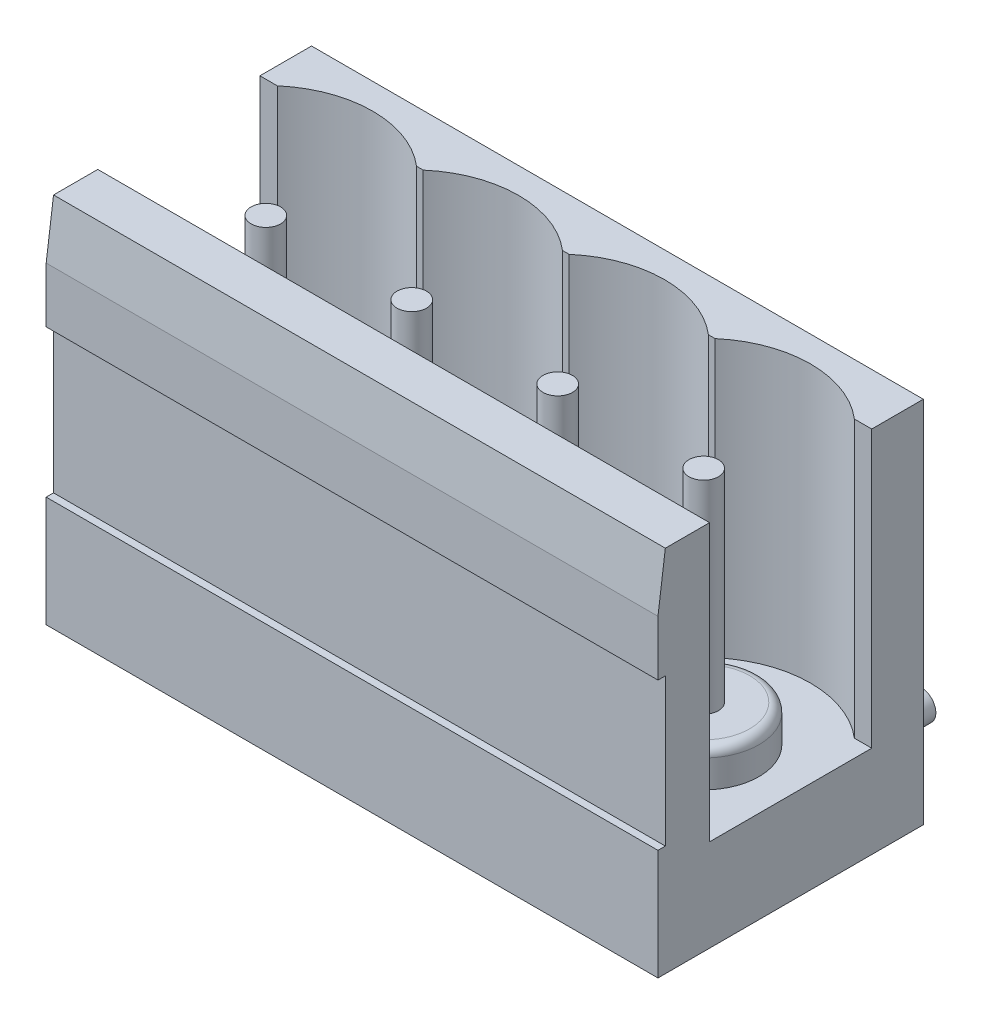
SolidWorks part; units mm, degrees
ref_plane "前视基准面" through (0, 0, 0) normal (0, 0, 1) x (1, 0, 0)
ref_plane "上视基准面" through (0, 0, 0) normal (0, 1, 0) x (1, 0, 0)
ref_plane "右视基准面" through (0, 0, 0) normal (1, 0, 0) x (0, 0, -1)
sketch "草图1" plane through (0, 0, 0) normal (0, 0, 1) x (1, 0, 0)
  line L0 (0, 0) -> (16.6, 0)
  line L1 (16.6, 0) -> (16.6, 10)
  line L2 (16.6, 10) -> (0, 10)
  line L3 (0, 10) -> (0, 0)
  dimension "D1" = 16.6
  dimension "D2" = 10
extrude "凸台-拉伸1" add sketch "草图1" along normal blind 7.2
sketch "草图2" plane through (16.6, 0, 0) normal (1, 0, 0) x (0, 0, -1)
  line L0 (-8.1771, 3) -> (-7, 3)
  line L1 (-7, 3) -> (-7, 7)
  line L2 (-7, 7) -> (-8.1771, 7)
  line L3 (-7.2, 0) -> (0, 0) construction
  line L4 (-7.2, 10) -> (0, 10) construction
  line L5 (-7.2, 0) -> (-7.2, 10) construction
  line L6 (-8.1771, 7) -> (-8.1771, 3)
  point P2 (-3.6, 0)
  dimension "D1" = 3
  dimension "D2" = 3
  dimension "D3" = 0.2
extrude "切除-拉伸1" cut sketch "草图2" against normal through all
sketch "草图3" plane through (16.6, 0, 0) normal (1, 0, 0) x (0, 0, -1)
  line L1 (-7.2, 10) -> (0, 10) construction
  line L2 (-7, 10) -> (-7.2, 8.5)
  line L3 (-7.2, 7) -> (-7.2, 10) construction
  line L4 (-7.2, 8.5) -> (-7.2, 10)
  line L5 (-7.2, 10) -> (-7, 10)
extrude "切除-拉伸2" cut sketch "草图3" against normal through all
sketch "草图6" plane through (0, 10, 0) normal (0, 1, 0) x (1, 0, 0)
  line L0 (0.3918, -1.4) -> (0, -1.4)
  line L6 (16.6, 0) -> (0, 0) construction
  line L8 (0.5, -0.8) -> (16.6, -0.8) construction
  line L9 (16.6, -7) -> (16.6, 0) construction
  line L10 (16.6, -1.4) -> (0.5, -1.4)
  line L11 (0.5, -5.8) -> (16.6, -5.8)
  line L12 (0.3918, -5.8) -> (0.5, -5.8)
  line L13 (0, -7) -> (0, 0) construction
  line L14 (0.3918, -0.8) -> (0.5, -0.8)
  line L15 (0.5, -1.4) -> (0.3918, -1.4)
  line L17 (0, -1.4) -> (-0.2811, -1.4)
  line L18 (-0.2811, -1.4) -> (-0.2811, -5.8)
  line L19 (-0.2811, -5.8) -> (0.3918, -5.8)
  line L20 (16.6, -5.8) -> (16.6, -1.4)
  line M1 (0, 0) -> (0, -7)
  line M3 (16.6, -7) -> (16.6, 0)
  dimension "D4" = 5
  dimension "D2" = 0.8
  dimension "D3" = 1.4
extrude "切除-拉伸4" cut sketch "草图6" against normal blind 7.5 contours L19 L12 L11 L10 L15 L0 M1 M3
sketch "草图12" plane through (0, 2.5, 0) normal (0, 1, 0) x (1, 0, 0)
  line L0 (16.6, -7.2) -> (16.6, 0) construction
  line L1 (16.6, -3.6) -> (0, -3.6) construction
  line L2 (0, -1.4) -> (0, -5.8) construction
  line L3 (8.3, -7) -> (8.3, 0) construction
  line L4 (0, -7) -> (16.6, -7) construction
  line L5 (16.6, 0) -> (0, 0) construction
  circle A0 centre (6.32, -3.6) radius 0.4
  circle A1 centre (2.36, -3.6) radius 0.4
  circle A2 centre (14.24, -3.6) radius 0.4
  circle A3 centre (10.28, -3.6) radius 0.4
  dimension "D1" = 0.8
  dimension "D2" = 3.96
  dimension "D3" = 2
extrude "凸台-拉伸8" add sketch "草图12" along normal blind 6.5
sketch "草图13" plane through (0, 2.5, 0) normal (0, 1, 0) x (1, 0, 0)
  circle A0 centre (14.24, -3.6) radius 1.5
  circle A1 centre (10.28, -3.6) radius 1.5
  circle A2 centre (6.32, -3.6) radius 1.5
  circle A3 centre (2.36, -3.6) radius 1.5
extrude "凸台-拉伸9" add sketch "草图13" along normal blind 1
fillet "圆角2" radius 0.25 4 edges at (2.36, 3.5, 5.1) (6.32, 3.5, 5.1) (10.28, 3.5, 5.1) (14.24, 3.5, 5.1)
sketch "草图14" plane through (0, 0, 0) normal (0, -1, 0) x (1, 0, 0)
  line L0 (0, 4.2) -> (16.6, 4.2) construction
  line L1 (0, 7.2) -> (0, 0) construction
  line L2 (16.6, 7.2) -> (16.6, 0) construction
  line L3 (0, 7.2) -> (16.6, 7.2) construction
  line L4 (8.3, 7.2) -> (8.3, 0) construction
  line L5 (0, 0) -> (16.6, 0) construction
  line L6 (10.28, 4.9755) -> (10.28, 2.6203) construction
  line L7 (9.78, 4.2) -> (9.78, 0)
  line L8 (10.78, 4.2) -> (10.78, 0)
  line L9 (9.78, 4.2) -> (10.78, 4.2)
  line L10 (9.78, 0) -> (10.78, 0)
  line L11 (10.78, 0) -> (10.788, 0.0286)
  line L12 (13.74, 4.2) -> (13.74, 0)
  line L13 (14.74, 4.2) -> (14.74, 0)
  line L14 (13.74, 4.2) -> (14.74, 4.2)
  line L15 (13.74, 0) -> (14.74, 0)
  line L16 (2.86, 0) -> (1.86, 0)
  line L17 (2.86, 4.2) -> (1.86, 4.2)
  line L18 (1.86, 4.2) -> (1.86, 0)
  line L19 (2.86, 4.2) -> (2.86, 0)
  line L20 (6.82, 0) -> (5.82, 0)
  line L21 (6.82, 4.2) -> (5.82, 4.2)
  line L22 (5.82, 4.2) -> (5.82, 0)
  line L23 (6.82, 4.2) -> (6.82, 0)
  line M1 (0, 0) -> (16.6, 0)
  dimension "D1" = 3
  dimension "D2" = 1.98
  dimension "D3" = 1
  dimension "D4" = 2
extrude "切除-拉伸7" cut sketch "草图14" against normal blind 1 contours L19 L17 L18 M1 | L23 L21 L22 M1 | L9 L7 L8 M1 | L14 L12 L13 M1
sketch "草图15" plane through (0, 0, 4.2) normal (0, 0, -1) x (-1, 0, 0)
  line L0 (-2.86, 0) -> (-1.86, 1) construction
  line L1 (-1.86, 0) -> (-2.86, 1) construction
  circle A0 centre (-2.36, 0.5) radius 0.4
  circle A1 centre (-6.32, 0.5) radius 0.4
  circle A2 centre (-10.28, 0.5) radius 0.4
  circle A3 centre (-14.24, 0.5) radius 0.4
extrude "凸台-拉伸10" add sketch "草图15" along normal blind 6.5
sketch "草图16" plane through (0, 10, 0) normal (0, 1, 0) x (1, 0, 0)
  line L0 (16.6, -0.7) -> (0, -0.7) construction
  line L1 (16.6, -1.4) -> (16.6, 0) construction
  line L2 (0, -1.4) -> (0, 0) construction
  line L3 (0.4706, -1.4) -> (4.2494, -1.4)
  line L4 (12.3506, -1.4) -> (16.1294, -1.4)
  line L5 (8.3906, -1.4) -> (12.1694, -1.4)
  line L6 (4.4306, -1.4) -> (8.2094, -1.4)
  arc A0 (16.1294, -1.4) -> (12.3506, -1.4) centre (14.24, -3.6) ccw
  arc A1 (12.1694, -1.4) -> (8.3906, -1.4) centre (10.28, -3.6) ccw
  arc A2 (8.2094, -1.4) -> (4.4306, -1.4) centre (6.32, -3.6) ccw
  arc A3 (4.2494, -1.4) -> (0.4706, -1.4) centre (2.36, -3.6) ccw
extrude "切除-拉伸9" cut sketch "草图16" against normal blind 7.5
